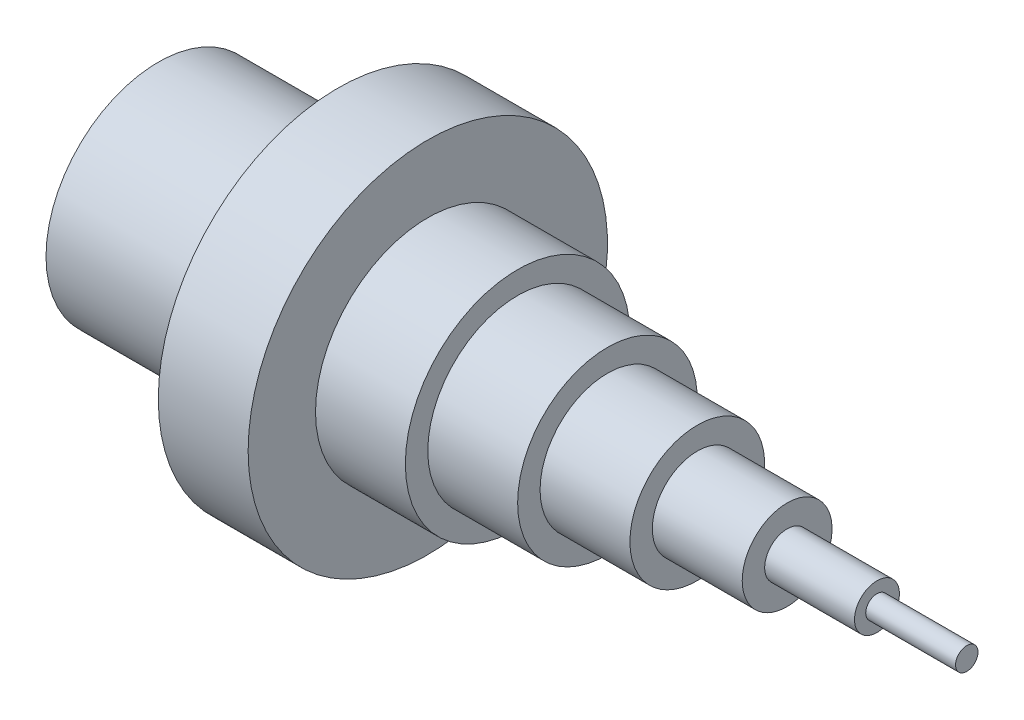
SolidWorks part; units mm, degrees
ref_plane "Alzado" through (0, 0, 0) normal (0, 0, 1) x (1, 0, 0)
ref_plane "Planta" through (0, 0, 0) normal (0, 1, 0) x (1, 0, 0)
ref_plane "Vista lateral" through (0, 0, 0) normal (1, 0, 0) x (0, 0, -1)
sketch "Croquis1" plane through (0, 0, 0) normal (0, 0, 1) x (1, 0, 0)
  line L0 (0, 0) -> (0, 2.5)
  line L1 (0, 2.5) -> (-20, 2.5)
  line L2 (-20, 2.5) -> (-20, 5)
  line L3 (-20, 5) -> (-40, 5)
  line L4 (-40, 5) -> (-40, 10)
  line L5 (-40, 10) -> (-60, 10)
  line L6 (-60, 10) -> (-60, 15)
  line L7 (-60, 15) -> (-80, 15)
  line L8 (-80, 15) -> (-80, 20)
  line L9 (-80, 20) -> (-100, 20)
  line L10 (-100, 20) -> (-100, 25)
  line L11 (-100, 25) -> (-120, 25)
  line L12 (-120, 25) -> (-120, 40)
  line L13 (-120, 40) -> (-140, 40)
  line L14 (-140, 40) -> (-140, 25)
  line L15 (-140, 25) -> (-180, 25)
  line L16 (-180, 25) -> (-180, 0)
  line L17 (-180, 0) -> (0, 0)
  dimension "D1" = 2.5
  dimension "D2" = 5
  dimension "D3" = 10
  dimension "D4" = 15
  dimension "D5" = 20
  dimension "D6" = 25
  dimension "D7" = 40
  dimension "D8" = 25
  dimension "D9" = 20
  dimension "D10" = 20
  dimension "D11" = 20
  dimension "D12" = 20
  dimension "D13" = 20
  dimension "D14" = 20
  dimension "D15" = 40
  dimension "D16" = 180
revolve "Revolución1" add sketch "Croquis1" angle 360 about L17
sketch "Croquis2" plane through (-180, 0, 0) normal (-1, 0, 0) x (0, 0, 1)
  circle A0 centre (0, 0) radius 20
  dimension "D1" = 40
extrude "Cortar-Extruir2" cut sketch "Croquis2" against normal blind 40
equation "\"Base\" = 5mm"
equation "\"D1@Croquis1\"=\"Base\"/2"
equation "\"D2@Croquis1\"=\"D1@Croquis1\"*2"
equation "\"D3@Croquis1\"=\"D2@Croquis1\"*2"
equation "\"D4@Croquis1\"=\"D2@Croquis1\"*3"
equation "\"D5@Croquis1\"=\"D3@Croquis1\"*2"
equation "\"D6@Croquis1\"=\"D1@Croquis1\"*10"
equation "\"D7@Croquis1\"=\"D5@Croquis1\"*2"
equation "\"D8@Croquis1\"=\"D6@Croquis1\""
equation "\"D9@Croquis1\"=\"Base\"*4"
equation "\"D10@Croquis1\"=\"D9@Croquis1\""
equation "\"D11@Croquis1\"=\"D9@Croquis1\""
equation "\"D12@Croquis1\"=\"D9@Croquis1\""
equation "\"D13@Croquis1\"=\"D9@Croquis1\""
equation "\"D14@Croquis1\"=\"D9@Croquis1\""
equation "\"D15@Croquis1\"=\"D9@Croquis1\"*2"
equation "\"D16@Croquis1\"=\"D9@Croquis1\"*9"
equation "\"D1@Croquis2\"=\"Base\"*8"
